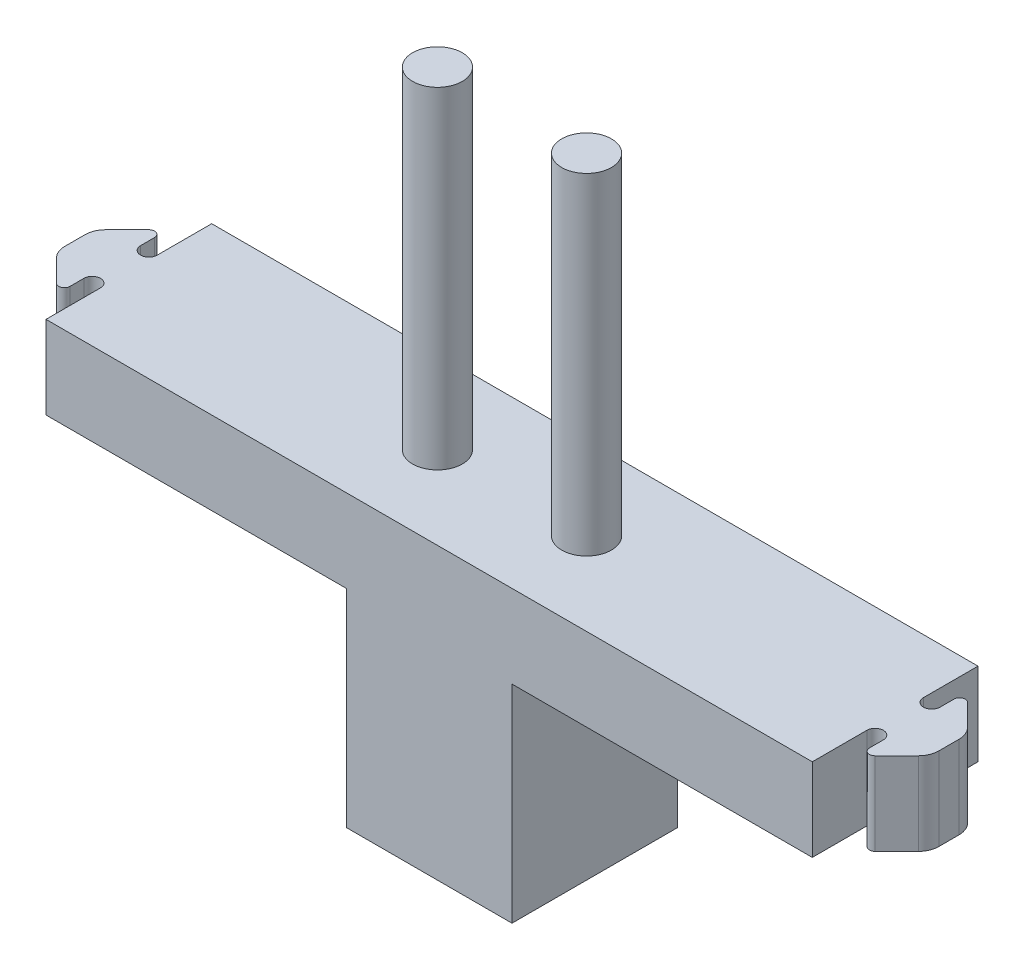
SolidWorks part; units mm, degrees
ref_plane "Front Plane" through (0, 0, 0) normal (0, 0, 1) x (1, 0, 0)
ref_plane "Top Plane" through (0, 0, 0) normal (0, 1, 0) x (1, 0, 0)
ref_plane "Right Plane" through (0, 0, 0) normal (1, 0, 0) x (0, 0, -1)
sketch "Sketch1" plane through (0, 0, 0) normal (0, 1, 0) x (1, 0, 0)
  line L0 (12.1572, -15.7678) -> (7.8138, -15.7678)
  line L1 (0, 0) -> (-117.475, 0)
  line L2 (0, 0) -> (0, -25.4)
  line L3 (0, -25.4) -> (-117.475, -25.4)
  line L4 (-117.475, 0) -> (-117.475, -25.4)
  line L13 (7.8138, -13.2278) -> (5.6802, -13.2278)
  line L14 (5.0695, -11.7535) -> (8.3922, -8.4308)
  line L15 (10.6437, -7.5166) -> (12.1572, -7.5166)
  line L16 (12.1572, -7.5166) -> (12.1572, -15.7678)
  arc A0 (7.8138, -15.7678) -> (7.8138, -13.2278) centre (7.8138, -14.4978) ccw
  arc A1 (5.6802, -13.2278) -> (5.0695, -11.7535) centre (5.6802, -12.3642) cw
  arc A2 (8.3922, -8.4308) -> (10.6437, -7.5166) centre (10.6216, -10.6915) cw
  point P18 (11.4004, -7.5166)
  dimension "D5" = 6.477
  dimension "D7" = 1.27
  dimension "D8" = 0.8636
  dimension "D9" = 3.175
  dimension "D1" = 117.475
  dimension "D2" = 25.4
  dimension "D3" = 4.3434
  dimension "D4" = 8.2512
  dimension "D6" = 45
  dimension "D10" = 2.54
  dimension "D11" = 3.4036
  dimension "D12" = 5.0763
  dimension "D13" = 1.5356
  dimension "D14" = 4.3434
  dimension "D15" = 4.0143
extrude "Boss-Extrude1" add sketch "Sketch1" along normal blind 12.7
sketch "Sketch3" plane through (0, 12.7, 0) normal (0, 1, 0) x (1, 0, 0)
  line L0 (0, 0) -> (-117.475, 0) construction
  line L1 (-114.3, 0) -> (-3.175, 0)
  line L2 (-114.3, 0) -> (-114.3, -25.4)
  line L3 (-114.3, -25.4) -> (-3.175, -25.4)
  line L4 (-3.175, 0) -> (-3.175, -25.4)
  line L5 (0, -25.4) -> (-117.475, -25.4) construction
  line L6 (0, -25.4) -> (-117.475, -25.4) construction
  circle A0 centre (-47.3075, -12.7) radius 3.81
  circle A1 centre (-70.1675, -12.7) radius 3.81
  point P8 (-58.7375, 0)
  point P11 (-58.7375, -25.4)
  dimension "D3" = 12.7
  dimension "D7" = 7.62
  dimension "D8" = 7.62
  dimension "D1" = 111.125
  dimension "D2" = 0
  dimension "D4" = 11.43
  dimension "D5" = 12.7
  dimension "D6" = 11.43
extrude "Boss-Extrude2" add sketch "Sketch3" along normal blind 50.8 contours A0 | A1
ref_plane "Plane1" through (-58.7375, 0, 0) normal (-1, 0, 0) x (0, 0, 1)
sketch "Sketch10" plane through (0, 12.7, 0) normal (0, 1, 0) x (1, 0, 0)
  line L5 (0, -12.7) -> (0, -8.3566)
  line L6 (2.54, -8.3566) -> (2.54, -6.223)
  line L7 (4.0143, -5.6123) -> (7.337, -8.935)
  line L8 (8.2512, -11.1865) -> (8.2512, -12.7)
  line L9 (8.2512, -12.7) -> (0, -12.7)
  line L10 (-58.7375, 3.4925) -> (-58.7375, -3.4925) construction
  line L11 (0, 0) -> (0, -25.4) construction
  line L12 (-117.475, -12.7) -> (-117.475, -8.3566)
  line L13 (-120.015, -8.3566) -> (-120.015, -6.223)
  line L14 (-121.4893, -5.6123) -> (-124.812, -8.935)
  line L15 (-125.7262, -11.1865) -> (-125.7262, -12.7)
  line L16 (-125.7262, -12.7) -> (-117.475, -12.7)
  arc A3 (0, -8.3566) -> (2.54, -8.3566) centre (1.27, -8.3566) ccw
  arc A4 (2.54, -6.223) -> (4.0143, -5.6123) centre (3.4036, -6.223) cw
  arc A5 (7.337, -8.935) -> (8.2512, -11.1865) centre (5.0763, -11.1644) cw
  arc A6 (-117.475, -8.3566) -> (-120.015, -8.3566) centre (-118.745, -8.3566) cw
  arc A7 (-120.015, -6.223) -> (-121.4893, -5.6123) centre (-120.8786, -6.223) ccw
  arc A8 (-124.812, -8.935) -> (-125.7262, -11.1865) centre (-122.5513, -11.1644) ccw
  point P2 (0, -12.7)
extrude "Boss-Extrude7" add sketch "Sketch10" against normal blind 12.7
mirror "Mirror1" about plane through (8.2512, 0, 12.7) normal (0, 0, 1) of "Boss-Extrude7"
sketch "Sketch12" plane through (0, 0, 0) normal (0, -1, 0) x (-1, 0, 0)
  line L0 (0, -25.4) -> (117.475, -25.4) construction
  line L1 (71.4375, -25.4) -> (46.0375, -25.4)
  line L2 (71.4375, -25.4) -> (71.4375, 0)
  line L3 (71.4375, 0) -> (46.0375, 0)
  line L4 (46.0375, -25.4) -> (46.0375, 0)
  line L5 (0, 0) -> (117.475, 0) construction
  point P8 (58.7375, 0)
  point P9 (58.7375, 0)
  dimension "D1" = 25.4
extrude "Boss-Extrude8" add sketch "Sketch12" along normal blind 31.75 contours L2 L1 L4 L3
